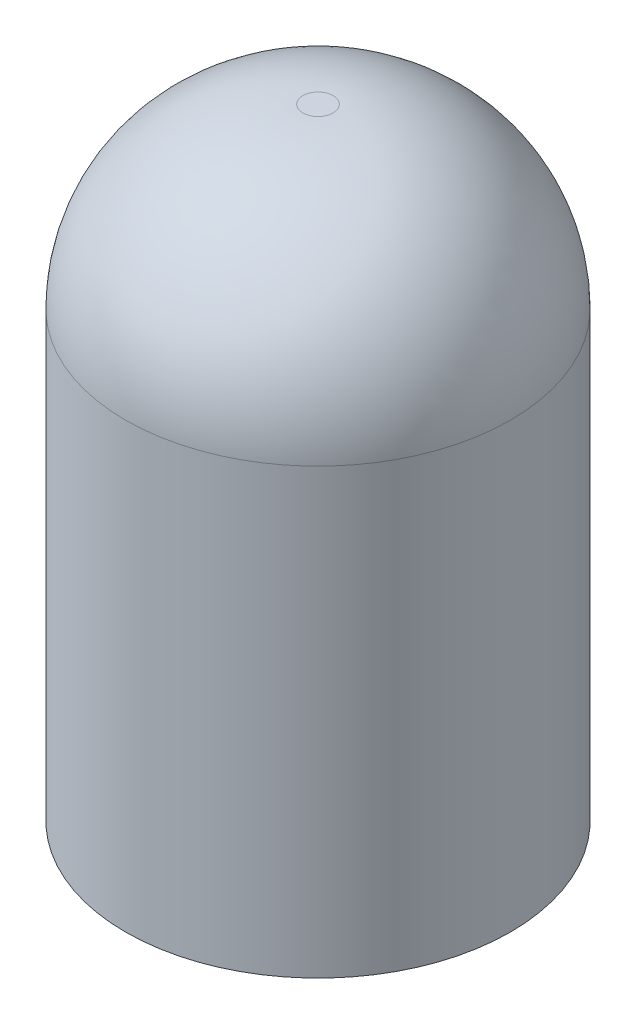
SolidWorks part; units mm, degrees
material "ABS PC"
ref_plane "Front Plane" through (0, 0, 0) normal (0, 0, 1) x (1, 0, 0)
ref_plane "Top Plane" through (0, 0, 0) normal (0, 1, 0) x (1, 0, 0)
ref_plane "Right Plane" through (0, 0, 0) normal (1, 0, 0) x (0, 0, -1)
sketch "Sketch1" plane through (0, 0, 0) normal (0, 1, 0) x (1, 0, 0)
  circle A0 centre (0, 0) radius 2.17
extrude "Boss-Extrude1" add sketch "Sketch1" along normal blind 7
fillet "Fillet3" radius 2 1 edges at (0, 7, 2.17)
